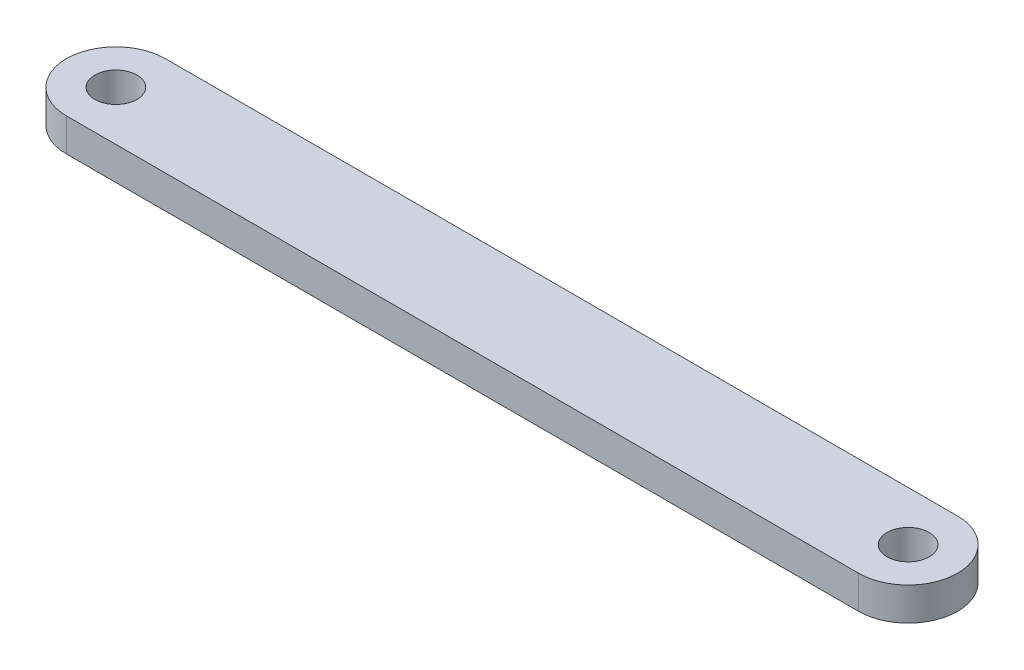
SolidWorks part; units mm, degrees
ref_plane "Front Plane" through (0, 0, 0) normal (0, 0, 1) x (1, 0, 0)
ref_plane "Top Plane" through (0, 0, 0) normal (0, 1, 0) x (1, 0, 0)
ref_plane "Right Plane" through (0, 0, 0) normal (1, 0, 0) x (0, 0, -1)
sketch "Sketch1" plane through (0, 0, 0) normal (0, 1, 0) x (1, 0, 0)
  line L1 (-49.6185, -5.6012) -> (26.5815, -5.6012)
  line L3 (-49.6185, 3.9238) -> (26.5815, 3.9238)
  arc A0 (26.5815, -5.6012) -> (26.5815, 3.9238) centre (26.5815, -0.8387) ccw
  arc A1 (-49.6185, 3.9238) -> (-49.6185, -5.6012) centre (-49.6185, -0.8387) ccw
  circle A2 centre (-49.6185, -0.8387) radius 2.032
  circle A3 centre (26.5815, -0.8387) radius 2.032
  point P0 (0, 0)
  dimension "D1" = 76.2
  dimension "D2" = 9.525
extrude "Extrude1" add sketch "Sketch1" along normal blind 3.175
